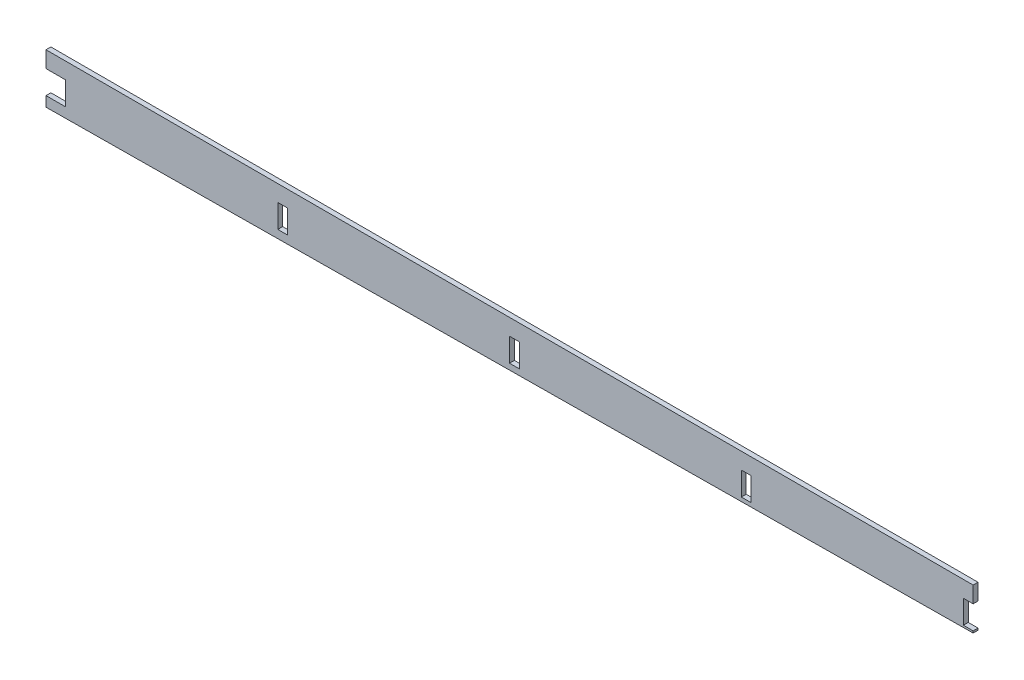
SolidWorks part; units mm, degrees
material "Balsa"
ref_plane "Front Plane" through (0, 0, 0) normal (0, 0, 1) x (1, 0, 0)
ref_plane "Top Plane" through (0, 0, 0) normal (0, 1, 0) x (1, 0, 0)
ref_plane "Right Plane" through (0, 0, 0) normal (1, 0, 0) x (0, 0, -1)
sketch "Sketch1" plane through (0, 0, 0) normal (0, 0, 1) x (1, 0, 0)
  line L0 (232.6268, 25.5278) -> (-69.6332, 22.8671)
  line L1 (-69.6332, 22.8671) -> (-69.6332, 26.153)
  line L2 (-69.6332, 26.153) -> (-63.2832, 26.153)
  line L3 (-63.2832, 26.153) -> (-63.2832, 33.773)
  line L4 (-63.2832, 33.773) -> (-69.6332, 33.773)
  line L5 (-69.6332, 33.773) -> (-69.6332, 39.0943)
  line L6 (-69.6332, 39.0943) -> (232.6268, 39.0943)
  line L7 (232.6268, 39.0943) -> (232.6268, 33.773)
  line L8 (232.6268, 33.773) -> (229.4518, 33.773)
  line L9 (229.4518, 33.773) -> (229.4518, 26.153)
  line L10 (229.4518, 26.153) -> (232.6268, 26.153)
  line L11 (232.6268, 26.153) -> (232.6268, 25.5278)
  line L12 (160.2368, 26.153) -> (157.0618, 26.153)
  line L13 (157.0618, 26.153) -> (157.0618, 33.773)
  line L14 (157.0618, 33.773) -> (160.2368, 33.773)
  line L15 (160.2368, 33.773) -> (160.2368, 26.153)
  line L16 (84.6718, 26.153) -> (81.4968, 26.153)
  line L17 (81.4968, 26.153) -> (81.4968, 33.773)
  line L18 (81.4968, 33.773) -> (84.6718, 33.773)
  line L19 (84.6718, 33.773) -> (84.6718, 26.153)
  line L20 (9.1068, 26.153) -> (5.9318, 26.153)
  line L21 (5.9318, 26.153) -> (5.9318, 33.773)
  line L22 (5.9318, 33.773) -> (9.1068, 33.773)
  line L23 (9.1068, 33.773) -> (9.1068, 26.153)
extrude "Boss-Extrude1" add sketch "Sketch1" along normal blind 1.5875
